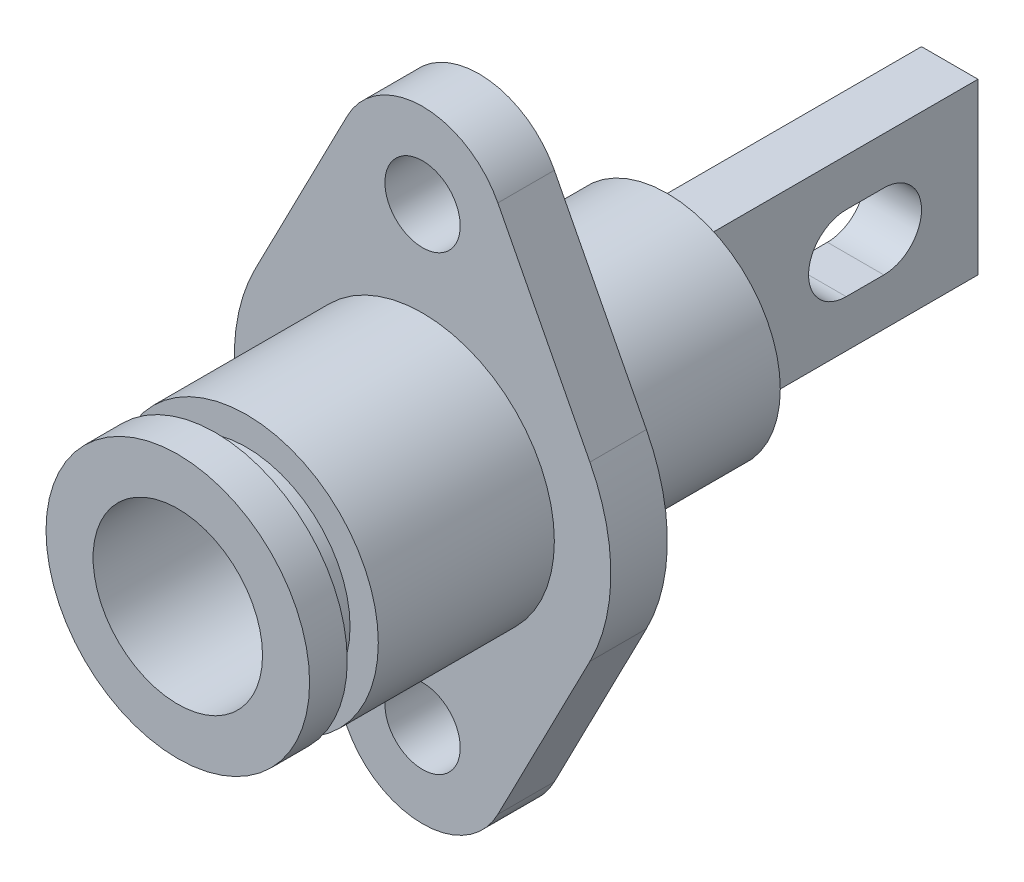
SolidWorks part; units mm, degrees
material "Custom Plastic"
ref_plane "X-Y Datum" through (0, 0, 0) normal (0, 0, 1) x (1, 0, 0)
ref_plane "X-Z Datum" through (0, 0, 0) normal (0, 1, 0) x (1, 0, 0)
ref_plane "Y-Z Datum" through (0, 0, 0) normal (1, 0, 0) x (0, 0, -1)
sketch "Sketch1" plane through (0, 0, 0) normal (0, 0, 1) x (1, 0, 0)
  line L0 (0, 17) -> (0, -17) construction
  line L1 (-10, 0) -> (10, 0) construction
  line L2 (-3.7696, 14.5084) -> (-8.8878, 4.5833)
  line L3 (3.7696, 14.5084) -> (8.8878, 4.5833)
  line L4 (3.7696, -14.5084) -> (8.8878, -4.5833)
  line L5 (-3.7696, -14.5084) -> (-8.8878, -4.5833)
  line L6 (0, 12) -> (0, -12) construction
  circle A0 centre (0, 0) radius 10
  circle A5 centre (0, 12) radius 2
  circle A6 centre (0, -12) radius 2
  circle A7 centre (0, 12) radius 4.5
  circle A8 centre (0, -12) radius 4.5
  point P4 (0, 0)
  point P8 (0, 0)
  point P26 (0, 0)
  dimension "D3" = 4
  dimension "D5" = 24
  dimension "D1" = 34
  dimension "D2" = 20
  dimension "D4" = 24
  dimension "D6" = 2.5
extrude "Boss-Extrude1" add sketch "Sketch1" along normal blind 3 contours A7 A0 A5 | A7 L2 A0 | A7 A0 L3 | A0 A8 A7 | A0 A7 | L5 A8 A0 | A8 A0 | A8 A0 A6 | A0 A8 L4
sketch "Sketch2" plane through (0, 0, 3) normal (0, 0, 1) x (1, 0, 0)
  circle A0 centre (0, 0) radius 7
  dimension "D1" = 14
extrude "Boss-Extrude2" add sketch "Sketch2" along normal blind 9.35
sketch "Sketch3" plane through (0, 0, 0) normal (0, 0, -1) x (-1, 0, 0)
  circle A0 centre (0, 0) radius 7.5
  dimension "D1" = 15
extrude "Boss-Extrude3" add sketch "Sketch3" along normal blind 0.5
sketch "Sketch4" plane through (0, 0, -0.5) normal (0, 0, -1) x (-1, 0, 0)
  line L1 (-1.5, 4.5) -> (1.5, 4.5)
  line L2 (-1.5, 4.5) -> (-1.5, -4.5)
  line L3 (-1.5, -4.5) -> (1.5, -4.5)
  line L4 (1.5, 4.5) -> (1.5, -4.5)
  line L5 (-1.5, 4.5) -> (1.5, -4.5) construction
  line L6 (-1.5, -4.5) -> (1.5, 4.5) construction
  point P0 (0, 0)
  dimension "D1" = 9
  dimension "D2" = 3
extrude "Boss-Extrude4" add sketch "Sketch4" along normal blind 24.5
sketch "Sketch5" plane through (0, 0, -0.5) normal (0, 0, -1) x (-1, 0, 0)
  circle A0 centre (0, 0) radius 6
  dimension "D1" = 12
extrude "Boss-Extrude5" add sketch "Sketch5" along normal blind 9.5
sketch "Sketch8" plane through (0, 0, 12.35) normal (0, 0, 1) x (1, 0, 0)
  circle A0 centre (0, 0) radius 5.5
extrude "Boss-Extrude6" add sketch "Sketch8" along normal blind 1.65
sketch "Sketch9" plane through (0, 0, 14) normal (0, 0, 1) x (1, 0, 0)
  circle A0 centre (0, 0) radius 7
extrude "Boss-Extrude7" add sketch "Sketch9" along normal blind 2
sketch "Sketch10" plane through (0, 0, 16) normal (0, 0, 1) x (1, 0, 0)
  circle A0 centre (0, 0) radius 4.5
extrude "Cut-Extrude1" cut sketch "Sketch10" against normal blind 25 contours A0
sketch "Sketch14" plane through (1.5, 0, 0) normal (1, 0, 0) x (0, 0, -1)
  line L0 (10, 0) -> (16, 0)
  line L1 (10, 4.5) -> (10, -4.5) construction
  line L2 (16, 0) -> (22, 0)
  line L3 (22, 0) -> (25, 0)
  line L4 (25, 4.5) -> (25, -4.5) construction
sketch "Sketch15" plane through (1.5, 0, 0) normal (1, 0, 0) x (0, 0, -1)
  line L0 (22, 0) -> (20, 0)
  line L1 (16, 0) -> (22, 0) construction
  line L2 (16, 0) -> (18, 0)
  line L3 (20, 0) -> (18, 0) construction
  line L4 (20, -2) -> (18, -2)
  line L5 (20, 2) -> (18, 2)
  arc A0 (20, -2) -> (20, 2) centre (20, 0) ccw
  arc A1 (18, 2) -> (18, -2) centre (18, 0) ccw
  point P8 (19, 0)
extrude "Cut-Extrude2" cut sketch "Sketch15" against normal blind 3 contours A0 L5 A1 L4
